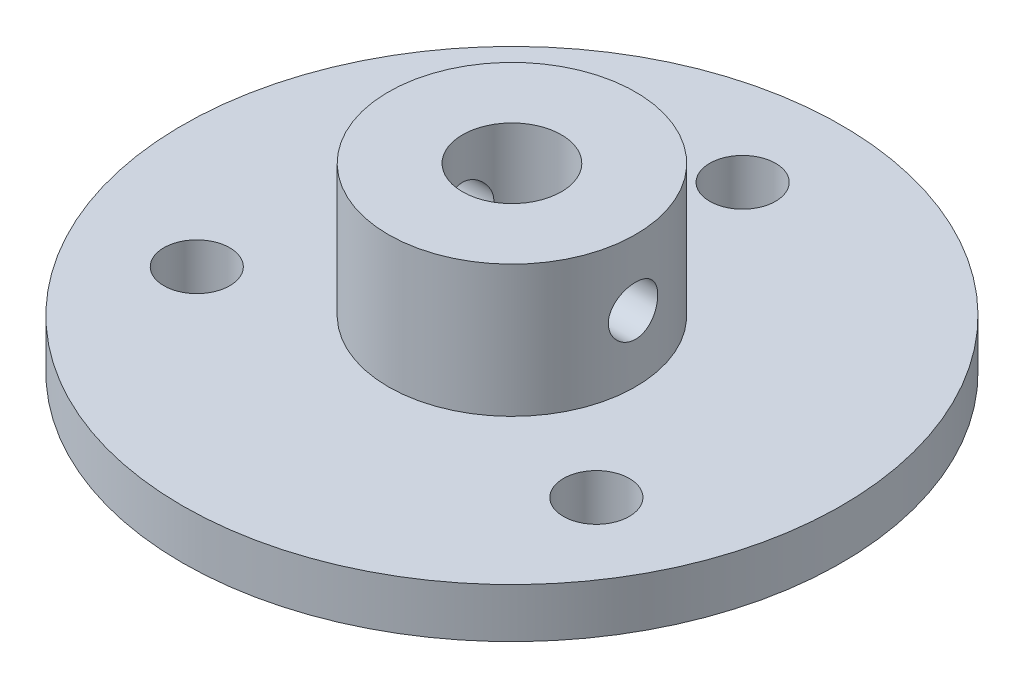
SolidWorks part; units mm, degrees
material "Bronce de aluminio"
ref_plane "Alzado" through (0, 0, 0) normal (0, 0, 1) x (1, 0, 0)
ref_plane "Planta" through (0, 0, 0) normal (0, 1, 0) x (1, 0, 0)
ref_plane "Vista lateral" through (0, 0, 0) normal (1, 0, 0) x (0, 0, -1)
sketch "Croquis1" plane through (0, 0, 0) normal (0, 1, 0) x (1, 0, 0)
  circle A0 centre (0, 0) radius 20
  circle A1 centre (0, 14) radius 2
  circle A2 centre (12.1244, -7) radius 2
  circle A4 centre (-12.1244, -7) radius 2
  circle A5 centre (0, 0) radius 3
  point P10 (0, 0.0282)
  dimension "D1" = 40
  dimension "D4" = 4
  dimension "D5" = 4
extrude "Saliente-Extruir1" add sketch "Croquis1" along normal blind 3
sketch "Croquis2" plane through (0, 3, 0) normal (0, 1, 0) x (1, 0, 0)
  circle A0 centre (0, 0) radius 7.5
  circle A1 centre (0, 0) radius 3
  dimension "D1" = 6
  dimension "D2" = 15
extrude "Saliente-Extruir2" add sketch "Croquis2" along normal blind 8
sketch "Croquis3" plane through (0, 0, 0) normal (1, 0, 0) x (0, 0, -1)
  line L0 (7.5, 11) -> (-7.5, 11) construction
  circle A0 centre (0, 7) radius 1.5
  dimension "D1" = 4
extrude "Cortar-Extruir1" cut sketch "Croquis3" against normal through all both and the other way through all
